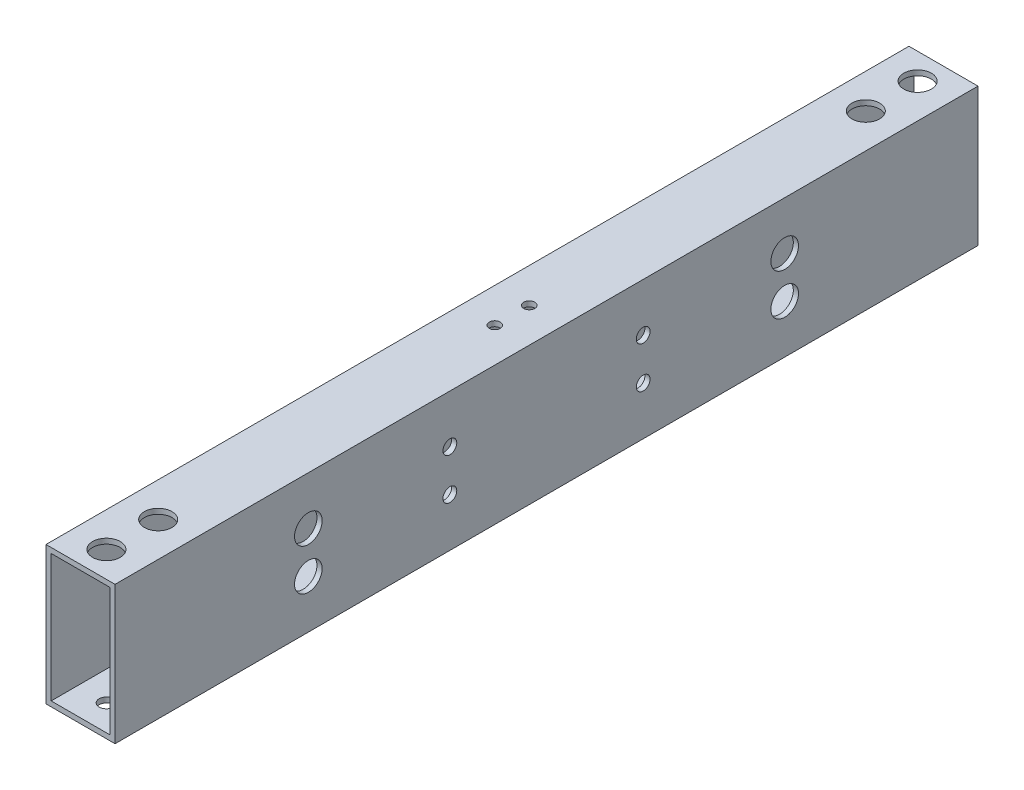
SolidWorks part; units mm, degrees
ref_plane "前视基准面" through (0, 0, 0) normal (0, 0, 1) x (1, 0, 0)
ref_plane "上视基准面" through (0, 0, 0) normal (0, 1, 0) x (1, 0, 0)
ref_plane "右视基准面" through (0, 0, 0) normal (1, 0, 0) x (0, 0, -1)
sketch "草图1" plane through (0, 0, 0) normal (0, 0, 1) x (1, 0, 0)
  line L1 (-10, -20) -> (10, -20)
  line L2 (-10, -20) -> (-10, 20)
  line L3 (-10, 20) -> (10, 20)
  line L4 (10, -20) -> (10, 20)
  line L5 (-10, -20) -> (10, 20) construction
  line L6 (-10, 20) -> (10, -20) construction
  line L7 (-8.5, -18.5) -> (8.5, -18.5)
  line L8 (-8.5, -18.5) -> (-8.5, 18.5)
  line L9 (-8.5, 18.5) -> (8.5, 18.5)
  line L10 (8.5, -18.5) -> (8.5, 18.5)
  line L11 (-8.5, -18.5) -> (8.5, 18.5) construction
  line L12 (-8.5, 18.5) -> (8.5, -18.5) construction
  point P0 (0, 0)
  point P5 (0, 0)
  dimension "D1" = 40
  dimension "D2" = 20
  dimension "D3" = 37
  dimension "D4" = 17
extrude "凸台-拉伸1" add sketch "草图1" against normal blind 250
sketch "草图2" plane through (-10, 0, 0) normal (-1, 0, 0) x (0, 0, 1)
  line L0 (-125, 20) -> (-125, -49980) construction
  line L1 (-250, 20) -> (0, 20) construction
  line L2 (0, 20) -> (0, -20) construction
  line L3 (-97, 6) -> (-56, 6) construction
  line L4 (-97, 6) -> (-97, -6) construction
  line L5 (-97, -6) -> (-56, -6) construction
  line L6 (-56, 6) -> (-56, -6) construction
  line L11 (-76.5, 6) -> (-76.5, -6) construction
  line L12 (-97, 0) -> (-56, 0) construction
  line L13 (-153, 0) -> (-194, 0) construction
  line L14 (-173.5, 6) -> (-173.5, -6) construction
  line L15 (-194, 6) -> (-194, -6) construction
  line L16 (-153, -6) -> (-194, -6) construction
  line L17 (-153, 6) -> (-153, -6) construction
  line L18 (-153, 6) -> (-194, 6) construction
  circle A0 centre (-97, 6) radius 2
  circle A8 centre (-56, 6) radius 2
  circle A9 centre (-56, -6) radius 2
  circle A10 centre (-97, -6) radius 2
  circle A11 centre (-153, -6) radius 2
  circle A12 centre (-194, -6) radius 2
  circle A13 centre (-194, 6) radius 2
  circle A14 centre (-153, 6) radius 2
  point P4 (-125, 20)
  point P25 (-76.5, 0)
  dimension "D4" = 4
  dimension "D1" = 12
  dimension "42" = 41
  dimension "D3" = 20
  dimension "70" = 56
extrude "切除-拉伸1" cut sketch "草图2" against normal through all
sketch "草图3" plane through (0, 20, 0) normal (0, 1, 0) x (1, 0, 0)
  line L0 (-10, 30) -> (49990, 30) construction
  line L2 (10, 0) -> (-10, 0) construction
  line L3 (0, 0) -> (0, 50000) construction
  line L4 (10, 125) -> (50010, 125) construction
  line L5 (10, 250) -> (10, 0) construction
  circle A0 centre (0, 22.5) radius 2.1
  circle A1 centre (0, 7.5) radius 2.1
  circle A2 centre (0, 242.5) radius 2.1
  circle A3 centre (0, 227.5) radius 2.1
  point P6 (0, 0)
  point P15 (10, 125)
  dimension "D2" = 4.2
  dimension "D3" = 4.2
  dimension "D1" = 30
  dimension "D4" = 15
  dimension "D5" = 7.5
extrude "切除-拉伸2" cut sketch "草图3" against normal through all
sketch "草图4" plane through (0, 20, 0) normal (0, 1, 0) x (1, 0, 0)
  line L0 (0, 250) -> (0, -49750) construction
  line L1 (10, 250) -> (-10, 250) construction
  line L2 (-10, 125) -> (49990, 125) construction
  line L3 (-10, 250) -> (-10, 0) construction
  circle A0 centre (0, 130) radius 1.6
  circle A1 centre (0, 120) radius 1.6
  point P4 (0, 250)
  point P9 (-10, 125)
  dimension "D1" = 3.2
  dimension "D2" = 10
extrude "切除-拉伸3" cut sketch "草图4" against normal through all
sketch "草图5" plane through (0, 20, 0) normal (0, 1, 0) x (1, 0, 0)
  line L0 (-10, 125) -> (49990, 125) construction
  line L1 (-10, 250) -> (-10, 0) construction
  line L2 (10, 250) -> (10, 0) construction
  circle A0 centre (0, 22.5) radius 4
  circle A1 centre (0, 7.5) radius 4
  circle A2 centre (0, 242.5) radius 4
  circle A3 centre (0, 227.5) radius 4
  point P10 (-10, 125)
  point P13 (10, 125)
  dimension "D1" = 8
  dimension "D2" = 8
extrude "切除-拉伸4" cut sketch "草图5" against normal blind 10
sketch "草图6" plane through (10, 0, 0) normal (1, 0, 0) x (0, 0, -1)
  circle A0 centre (56, 6) radius 4
  circle A1 centre (56, -6) radius 4
  circle A2 centre (194, 6) radius 4
  circle A3 centre (194, -6) radius 4
  dimension "D1" = 8
extrude "切除-拉伸5" cut sketch "草图6" against normal blind 10
equation "\"3。2\"=3.21956"
